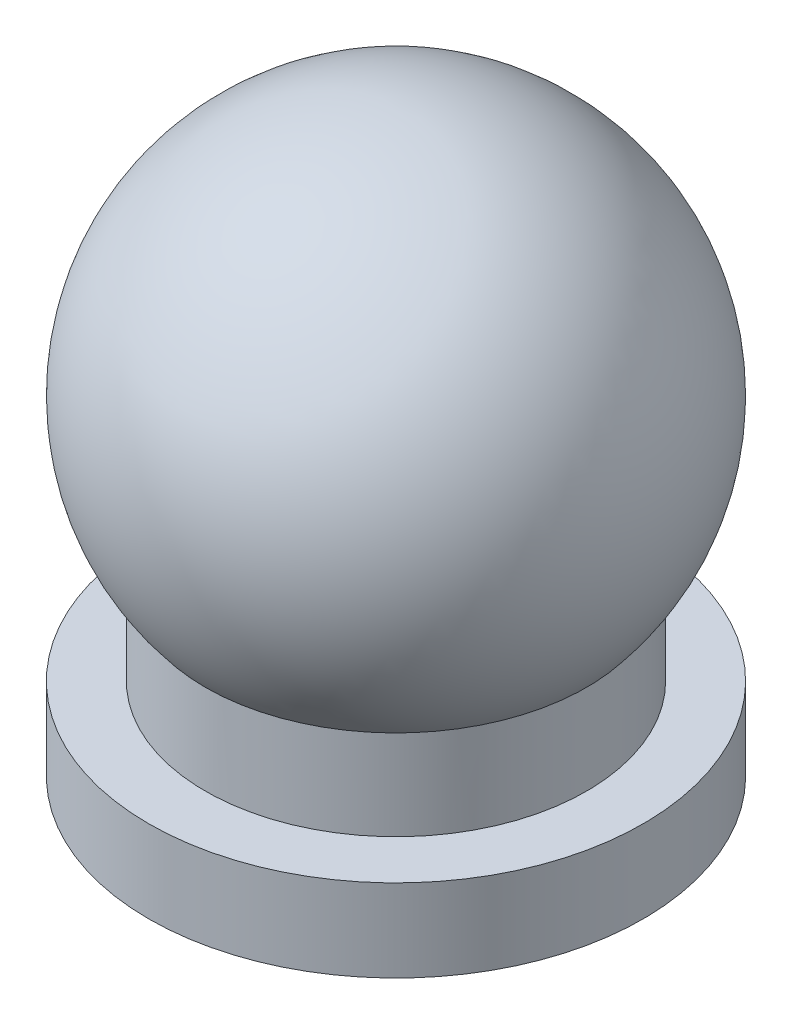
SolidWorks part; units mm, degrees
ref_plane "Front Plane" through (0, 0, 0) normal (0, 0, 1) x (1, 0, 0)
ref_plane "Top Plane" through (0, 0, 0) normal (0, 1, 0) x (1, 0, 0)
ref_plane "Right Plane" through (0, 0, 0) normal (1, 0, 0) x (0, 0, -1)
sketch "Sketch1" plane through (0, 0, 0) normal (0, 1, 0) x (1, 0, 0)
  circle A0 centre (0, 0) radius 3
  dimension "D1" = 6
extrude "Boss-Extrude1" add sketch "Sketch1" along normal blind 1
sketch "Sketch3" plane through (0, 0, 0) normal (1, 0, 0) x (0, 0, -1)
  line L5 (0, 1) -> (0, 4)
  line L6 (3, 1) -> (-3, 1) construction
  line L8 (0, 1) -> (-1.1569, 1)
  line L9 (0, 1) -> (-2.3138, 1)
  line L10 (0, 4) -> (0, 7)
  line L12 (-2.3138, 2.0905) -> (-2.3138, 1)
  arc A4 (0, 7) -> (-3, 4) centre (0, 4) ccw
  arc A5 (0, 7) -> (-2.3138, 2.0905) centre (0, 4) ccw
revolve "Revolve2" add sketch "Sketch3" angle 360 about L10
sketch "Sketch4" plane through (0, 0, 0) normal (0, -1, 0) x (1, 0, 0)
  circle A0 centre (0, 0) radius 1.5
extrude "Cut-Extrude1" cut sketch "Sketch4" against normal blind 5.5
